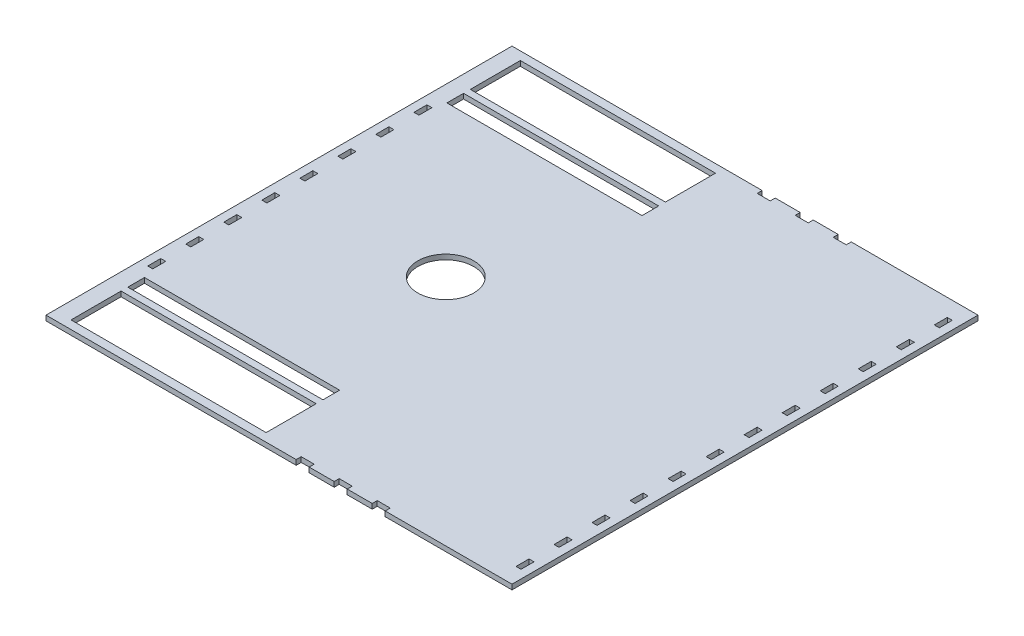
SolidWorks part; units mm, degrees
material "ENPH 253 Hardboard"
ref_plane "Front Plane" through (0, 0, 0) normal (0, 0, 1) x (1, 0, 0)
ref_plane "Top Plane" through (0, 0, 0) normal (0, 1, 0) x (1, 0, 0)
ref_plane "Right Plane" through (0, 0, 0) normal (1, 0, 0) x (0, 0, -1)
sketch "Sketch1" plane through (0, 0, 0) normal (0, 1, 0) x (1, 0, 0)
  line L0 (0, -139.7) -> (0, 139.7) construction
  line L1 (-139.7, 139.7) -> (139.7, 139.7)
  line L2 (-139.7, 139.7) -> (-139.7, -139.7)
  line L3 (-139.7, -139.7) -> (139.7, -139.7)
  line L4 (139.7, 139.7) -> (139.7, -139.7)
  line L5 (-139.7, 139.7) -> (139.7, -139.7) construction
  line L6 (-139.7, -139.7) -> (139.7, 139.7) construction
  line L7 (-129.7, 134.7) -> (-12.7, 134.7)
  line L8 (-129.7, 134.7) -> (-129.7, 104.7)
  line L9 (-129.7, 104.7) -> (-12.7, 104.7)
  line L10 (-12.7, 134.7) -> (-12.7, 104.7)
  line L12 (-139.7, 0) -> (139.7, 0) construction
  line L22 (-129.7, -104.7) -> (-12.7, -104.7)
  line L23 (-12.7, -134.7) -> (-12.7, -104.7)
  line L24 (-129.7, -134.7) -> (-12.7, -134.7)
  line L25 (-129.7, -134.7) -> (-129.7, -104.7)
  point P0 (0, 0)
  dimension "D1" = 279.4
  dimension "D2" = 279.4
  dimension "D3" = 5
  dimension "D4" = 30
  dimension "D5" = 117
  dimension "D6" = 10
extrude "Boss-Extrude1" add sketch "Sketch1" along normal blind 3
sketch "Sketch2" plane through (0, 3, 0) normal (0, 1, 0) x (1, 0, 0)
  line L0 (-139.7, 139.7) -> (-139.7, -139.7) construction
  line L1 (-129.7, 100.65) -> (-12.7, 100.65)
  line L2 (-129.7, 100.65) -> (-129.7, 90.65)
  line L3 (-129.7, 90.65) -> (-12.7, 90.65)
  line L4 (-12.7, 100.65) -> (-12.7, 90.65)
  line L5 (139.7, 139.7) -> (-139.7, 139.7) construction
  dimension "D1" = 10
  dimension "D2" = 39.05
  dimension "D3" = 10
  dimension "D4" = 117
extrude "Cut-Extrude1" cut sketch "Sketch2" against normal blind 10
mirror "Mirror1" about plane through (0, 0, 0) normal (0, 0, 1) of "Cut-Extrude1"
sketch "Sketch3" plane through (0, 0, 0) normal (0, -1, 0) x (-1, 0, 0)
  line L0 (-139.7, -139.7) -> (-139.7, 139.7) construction
  line L1 (-134.7, 129.3) -> (-131.7, 129.3)
  line L2 (-134.7, 129.3) -> (-134.7, 121.5)
  line L3 (-134.7, 121.5) -> (-131.7, 121.5)
  line L4 (-131.7, 129.3) -> (-131.7, 121.5)
  line L5 (-139.7, 139.7) -> (139.7, 139.7) construction
  dimension "D1" = 5
  dimension "D2" = 10.4
  dimension "D3" = 7.8
  dimension "D4" = 3
extrude "Cut-Extrude2" cut sketch "Sketch3" against normal through all
pattern_linear "LPattern1" count 12 spacing 22.8 along (0, 0, 1) of "Cut-Extrude2"
sketch "Sketch5" plane through (0, 0, 0) normal (0, -1, 0) x (1, 0, 0)
  line L0 (139.7, -139.7) -> (-139.7, -139.7) construction
  line L1 (55.9, -139.7) -> (63.7, -139.7)
  line L2 (55.9, -139.7) -> (55.9, -136.7)
  line L3 (55.9, -136.7) -> (63.7, -136.7)
  line L4 (63.7, -139.7) -> (63.7, -136.7)
  line L5 (139.7, 139.7) -> (139.7, -139.7) construction
  dimension "D1" = 76
  dimension "D2" = 7.8
  dimension "D3" = 3
extrude "Cut-Extrude3" cut sketch "Sketch5" against normal through all
pattern_linear "LPattern2" count 3 spacing 22.8 along (-1, 0, 0) of "Cut-Extrude3"
mirror "Mirror2" about plane through (0, 0, 0) normal (0, 0, 1) of "LPattern2", "Cut-Extrude3"
sketch "Sketch6" plane through (0, 0, 0) normal (0, -1, 0) x (1, 0, 0)
  line L0 (10.3, -139.7) -> (-139.7, -139.7) construction
  line L1 (-134.7, -83.7) -> (-131.7, -83.7)
  line L2 (-134.7, -83.7) -> (-134.7, -75.9)
  line L3 (-134.7, -75.9) -> (-131.7, -75.9)
  line L4 (-131.7, -83.7) -> (-131.7, -75.9)
  line L5 (-139.7, -139.7) -> (-139.7, 139.7) construction
  dimension "D1" = 56
  dimension "D2" = 5
  dimension "D3" = 3
  dimension "D4" = 7.8
extrude "Cut-Extrude4" cut sketch "Sketch6" against normal through all
pattern_linear "LPattern3" count 8 spacing 22.8 along (0, 0, 1) of "Cut-Extrude4"
sketch "Sketch7" plane through (0, 0, 0) normal (0, -1, 0) x (-1, 0, 0)
  line L0 (129.7, 90.65) -> (12.7, 90.65) construction
  line L1 (139.7, 139.7) -> (139.7, -139.7) construction
  circle A0 centre (39.7, 0) radius 16.75
  dimension "D1" = 33.5
  dimension "D2" = 100
  dimension "D3" = 90.65
extrude "Cut-Extrude5" cut sketch "Sketch7" against normal through all
